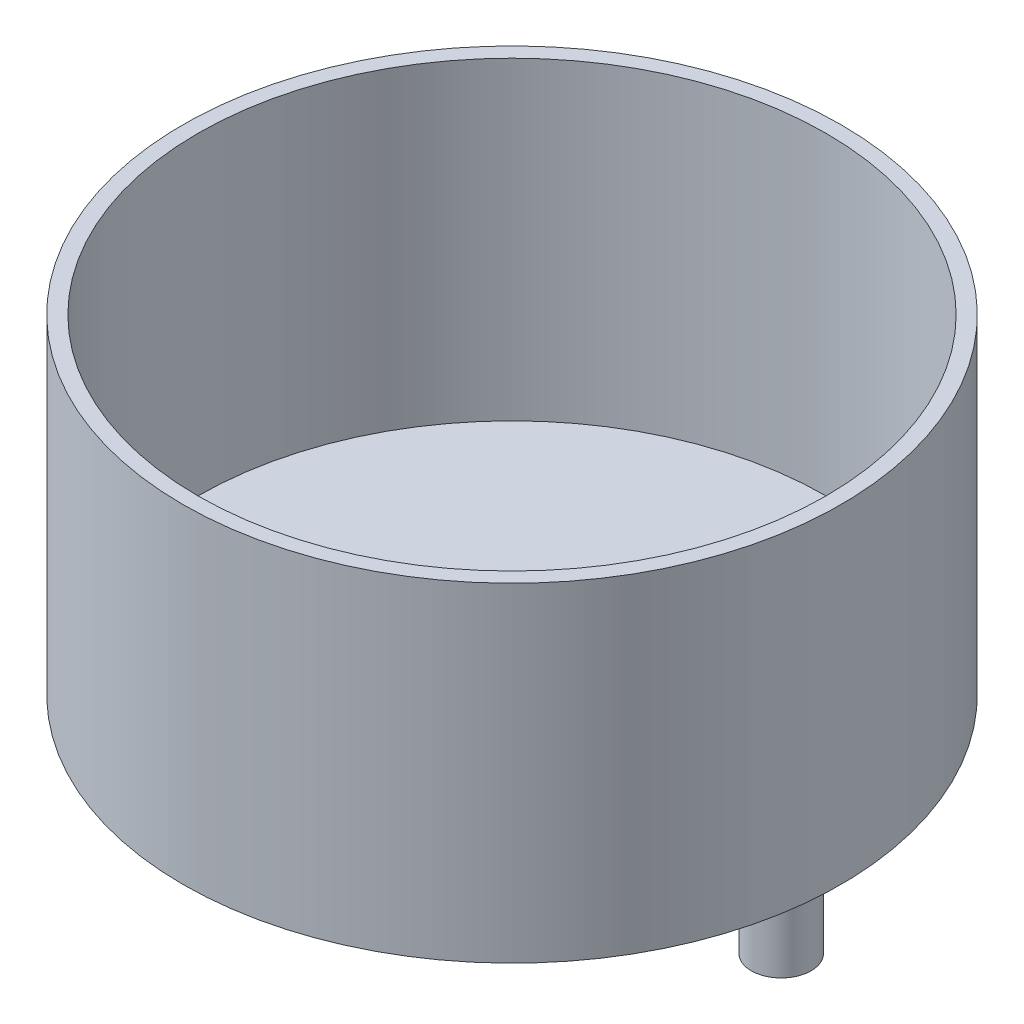
SolidWorks part; units mm, degrees
ref_plane "Front Plane" through (0, 0, 0) normal (0, 0, 1) x (1, 0, 0)
ref_plane "Top Plane" through (0, 0, 0) normal (0, 1, 0) x (1, 0, 0)
ref_plane "Right Plane" through (0, 0, 0) normal (1, 0, 0) x (0, 0, -1)
sketch "Compartment" plane through (0, 0, 0) normal (0, 0, 1) x (1, 0, 0)
  line L3 (110, -80) -> (0, -80)
  line L6 (105, 30) -> (110, 30)
  line L9 (105, 30) -> (105, -75)
  line L10 (105, -75) -> (0, -75)
  line L11 (0, -75) -> (0, -80)
  line L14 (110, 30) -> (110, -80)
  dimension "D1" = 105
  dimension "D2" = 5
  dimension "D5" = 105
  dimension "D6" = 5
  dimension "D9" = 80
ref_axis "Axis1" through (0, 0, 0) along (0, 1, 0)
revolve "Revolve1" add sketch "Compartment" angle 360 about axis through (0, 0, 0) along (0, 1, 0)
sketch "Motor Hole" plane through (0, -80, 0) normal (0, -1, 0) x (1, 0, 0)
  circle A0 centre (0, 0) radius 4.5
  dimension "D1" = 9
extrude "Cut-Extrude2" cut sketch "Motor Hole" against normal up to next
sketch "Stablizing poles" plane through (0, -80, 0) normal (0, -1, 0) x (1, 0, 0)
  circle A0 centre (-90, 0) radius 10
  circle A1 centre (90, 0) radius 10
  dimension "D1" = 20
  dimension "D2" = 90
  dimension "D3" = 90
extrude "Boss-Extrude1" add sketch "Stablizing poles" along normal blind 30
